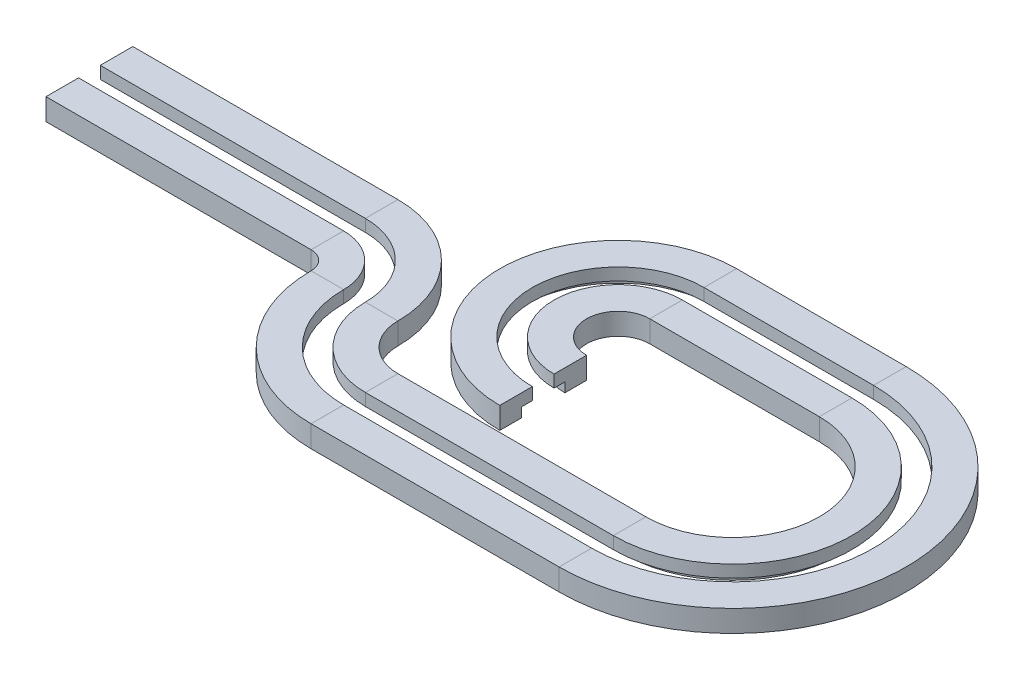
SolidWorks part; units mm, degrees
ref_plane "Front Plane" through (0, 0, 0) normal (0, 0, 1) x (1, 0, 0)
ref_plane "Top Plane" through (0, 0, 0) normal (0, 1, 0) x (1, 0, 0)
ref_plane "Right Plane" through (0, 0, 0) normal (1, 0, 0) x (0, 0, -1)
sketch "Sketch1" plane through (0, 0, 0) normal (1, 0, 0) x (0, 0, -1)
  line L0 (-0.9412, 0) -> (0.9412, 0) construction
  line L1 (0, 0) -> (0, 27413.7817) construction
  line L2 (16, -16) -> (32, -16)
  line L3 (-32, -16) -> (-16, -16)
  line L4 (-32, -16) -> (-32, 0)
  line L6 (32, -16) -> (32, 0)
  line L7 (8, -9) -> (16, -9)
  line L8 (8, 0) -> (32, 0)
  line L10 (-16, -16) -> (-16, -9)
  line L11 (-16, -9) -> (-8, -9)
  line L12 (16, -16) -> (16, -9)
  line L14 (-8, -9) -> (-8, 0)
  line L15 (-32, 0) -> (-8, 0)
  line L16 (8, -9) -> (8, 0)
  point P5 (0, 0)
  point P19 (16, -12.5)
  dimension "D1" = 64
  dimension "D3" = 7
  dimension "D4" = 32
  dimension "D5" = 16
  dimension "D6" = 16
sketch "Sketch3" plane through (0, 0, 0) normal (0, 1, 0) x (1, 0, 0)
  line L0 (0, 0) -> (195.4027, 0)
  line L1 (306.5246, -111.1219) -> (489.3392, -111.1219)
  line L2 (489.3392, 80.7187) -> (364.3281, 80.7187)
  arc A0 (195.4027, 0) -> (240.8788, -45.476) centre (195.4027, -45.476) cw
  arc A1 (240.8788, -45.476) -> (306.5246, -111.1219) centre (306.5246, -45.476) ccw
  arc A2 (489.3392, -111.1219) -> (489.3392, 80.7187) centre (489.3392, -15.2016) ccw
  arc A3 (364.3281, 80.7187) -> (364.3281, -29.8506) centre (364.3281, 25.434) ccw
sweep "Sweep1" add profiles "Sketch1" path "Sketch3"
sketch "Sketch5" plane through (0, 0, 0) normal (0, 1, 0) x (1, 0, 0)
  line L0 (489.3392, 72.7187) -> (364.3281, 72.7187) construction
  line L1 (306.5246, -103.1219) -> (489.3392, -103.1219) construction
  line L2 (0, 8) -> (195.4027, 8) construction
  line L3 (489.3392, 72.7187) -> (364.3281, 72.7187)
  line L4 (306.5246, -103.1219) -> (489.3392, -103.1219)
  line L5 (0, 8) -> (195.4027, 8)
  line L6 (0, 0) -> (195.4027, 0)
  line L7 (306.5246, -111.1219) -> (489.3392, -111.1219)
  line L8 (489.3392, 80.7187) -> (364.3281, 80.7187)
  arc A0 (364.3281, 72.7187) -> (364.3281, -21.8506) centre (364.3281, 25.434) ccw construction
  arc A1 (489.3392, -103.1219) -> (489.3392, 72.7187) centre (489.3392, -15.2016) ccw construction
  arc A2 (248.8788, -45.476) -> (306.5246, -103.1219) centre (306.5246, -45.476) ccw construction
  arc A3 (248.8788, -45.476) -> (195.4027, 8) centre (195.4027, -45.476) ccw construction
  arc A4 (364.3281, 72.7187) -> (364.3281, -21.8506) centre (364.3281, 25.434) ccw
  arc A5 (489.3392, -103.1219) -> (489.3392, 72.7187) centre (489.3392, -15.2016) ccw
  arc A6 (248.8788, -45.476) -> (306.5246, -103.1219) centre (306.5246, -45.476) ccw
  arc A7 (248.8788, -45.476) -> (195.4027, 8) centre (195.4027, -45.476) ccw
  arc A8 (240.8788, -45.476) -> (195.4027, 0) centre (195.4027, -45.476) ccw
  arc A9 (240.8788, -45.476) -> (306.5246, -111.1219) centre (306.5246, -45.476) ccw
  arc A10 (489.3392, -111.1219) -> (489.3392, 80.7187) centre (489.3392, -15.2016) ccw
  arc A11 (364.3281, 80.7187) -> (364.3281, -29.8506) centre (364.3281, 25.434) ccw
  dimension "D1" = 8
